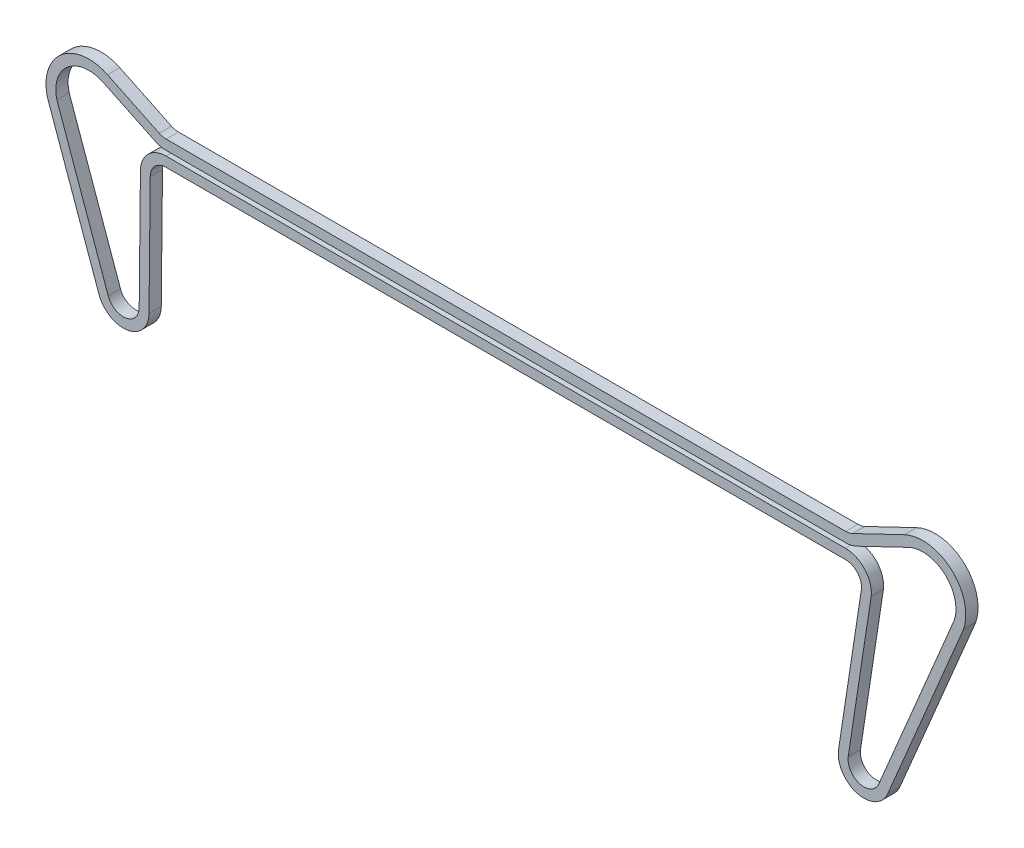
SolidWorks part; units mm, degrees
ref_plane "Front Plane" through (0, 0, 0) normal (0, 0, 1) x (1, 0, 0)
ref_plane "Top Plane" through (0, 0, 0) normal (0, 1, 0) x (1, 0, 0)
ref_plane "Right Plane" through (0, 0, 0) normal (1, 0, 0) x (0, 0, -1)
ref_plane "Plane1" through (0, 0, -5) normal (0, 0, -1) x (-1, 0, 0)
sketch "Sketch1" plane through (0, 0, -5) normal (0, 0, -1) x (-1, 0, 0)
  line L0 (-25, -11.5096) -> (-24.5, -60.0109)
  line L1 (-4.1089, -63.5237) -> (16.8918, -4.5735)
  line L2 (-7.5738, 15.7762) -> (-28.6869, 5.6403)
  line L3 (-31.5, 5) -> (-308.5, 5)
  line L4 (-311.3131, 5.6403) -> (-332.4262, 15.7762)
  line L5 (-356.5916, -5.5649) -> (-325.6789, -79.0705)
  line L6 (-305.6202, -73.4159) -> (-314.9612, -12.2092)
  line L7 (-308.5, -5) -> (-31.5, -5)
  line L8 (-31.5, -1) -> (-308.5, -1)
  line L9 (-318.9266, -12.7393) -> (-309.5744, -74.0194)
  line L10 (-321.9917, -77.5198) -> (-352.8429, -4.1606)
  line L11 (-334.1574, 12.1702) -> (-313.0443, 2.0343)
  line L12 (-308.5, 1) -> (-31.5, 1)
  line L13 (-26.9557, 2.0343) -> (-5.8426, 12.1702)
  line L14 (13.0681, -3.3874) -> (-7.8769, -62.1813)
  line L15 (-20.5, -59.9904) -> (-21, -11.4891)
  arc A0 (-31.5, -5) -> (-25, -11.5096) centre (-31.5, -11.5) cw
  arc A1 (-24.5, -60.0109) -> (-4.1089, -63.5237) centre (-14, -60) ccw
  arc A2 (16.8918, -4.5735) -> (-7.5738, 15.7762) centre (0, 0) ccw
  arc A3 (-28.6869, 5.6403) -> (-31.5, 5) centre (-31.5, 11.5) cw
  arc A4 (-308.5, 5) -> (-311.3131, 5.6403) centre (-308.5, 11.5) cw
  arc A5 (-332.4262, 15.7762) -> (-356.5916, -5.5649) centre (-340, 0) ccw
  arc A6 (-325.6789, -79.0705) -> (-305.6202, -73.4159) centre (-316, -75) ccw
  arc A7 (-314.9612, -12.2092) -> (-308.5, -5) centre (-308.5, -11.5) cw
  arc A8 (-21, -11.4891) -> (-31.5, -1) centre (-31.5, -11.5) ccw
  arc A9 (-308.5, -1) -> (-318.9266, -12.7393) centre (-308.5, -11.5) ccw
  arc A10 (-309.5744, -74.0194) -> (-321.9917, -77.5198) centre (-316, -75) cw
  arc A11 (-352.8429, -4.1606) -> (-334.1574, 12.1702) centre (-340, 0) cw
  arc A12 (-313.0443, 2.0343) -> (-308.5, 1) centre (-308.5, 11.5) ccw
  arc A13 (-31.5, 1) -> (-26.9557, 2.0343) centre (-31.5, 11.5) ccw
  arc A14 (-5.8426, 12.1702) -> (13.0681, -3.3874) centre (0, 0) cw
  arc A15 (-7.8769, -62.1813) -> (-20.5, -59.9904) centre (-14, -60) cw
extrude "Boss-Extrude1" add sketch "Sketch1" against normal blind 5
